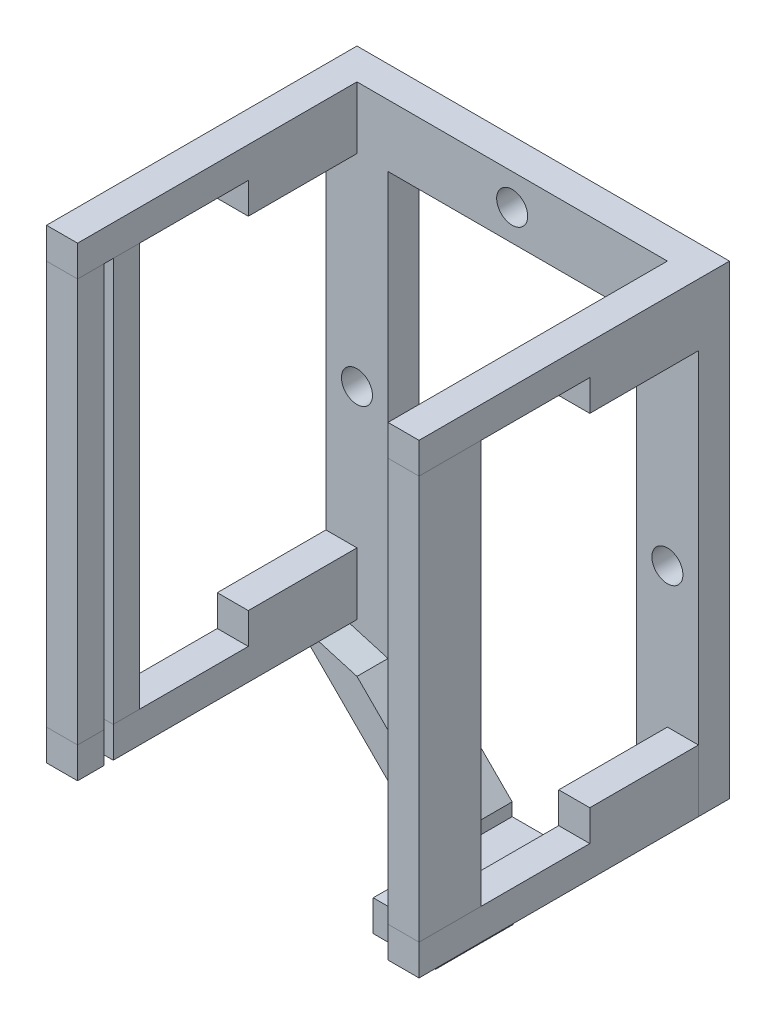
SolidWorks part; units mm, degrees
ref_plane "Plan de face" through (0, 0, 0) normal (0, 0, 1) x (1, 0, 0)
ref_plane "Plan de dessus" through (0, 0, 0) normal (0, 1, 0) x (1, 0, 0)
ref_plane "Plan de droite" through (0, 0, 0) normal (1, 0, 0) x (0, 0, -1)
sketch "Esquisse2" plane through (0, 0, 0) normal (0, 0, 1) x (1, 0, 0)
  line L0 (-70, 50) -> (-20, 0)
  line L1 (0, 0) -> (-20, 0)
  line L2 (50, 50) -> (50, 200)
  line L3 (50, 200) -> (-70, 200)
  line L4 (-70, 50) -> (-70, 200)
  line L5 (50, 50) -> (0, 0)
  line L6 (-50, 180) -> (30, 180)
  line L7 (30, 180) -> (30, 44.1421)
  line L8 (30, 44.1421) -> (0, 14.1421)
  line L9 (0, 14.1421) -> (-20, 14.1421)
  line L10 (-20, 14.1421) -> (-50, 44.1421)
  line L11 (-50, 44.1421) -> (-50, 180)
  line L12 (-20, 14.1421) -> (-20, 0) construction
  line L13 (0, 14.1421) -> (0, 0) construction
  line L14 (-50, 44.1421) -> (-70, 50) construction
  line L15 (30, 44.1421) -> (50, 50) construction
  dimension "D1" = 120
  dimension "D2" = 200
  dimension "D3" = 45
  dimension "D4" = 50
  dimension "D5" = 45
  dimension "D6" = 50
  dimension "D7" = 20
  dimension "D8" = 20
  dimension "D9" = 10
  dimension "D10" = 10
  dimension "D11" = 20
extrude "Extrusion2" add sketch "Esquisse2" along normal blind 20
sketch "Esquisse3" plane through (0, 0, 20) normal (0, 0, 1) x (1, 0, 0)
  line L0 (50, 200) -> (-70, 200) construction
  line L1 (-50, 180) -> (39.728, 180)
  line L2 (-50, 180) -> (-50, 200)
  line L3 (-50, 200) -> (39.728, 200)
  line L4 (39.728, 180) -> (39.728, 200)
  line L6 (30, 44.1421) -> (30, 180) construction
extrude "Enlèv. mat.-Extru.1" cut sketch "Esquisse3" against normal blind 10
sketch "Esquisse5" plane through (0, 0, 10) normal (0, 0, 1) x (1, 0, 0)
  line L0 (-70, 50) -> (-50, 44.1421)
  line L1 (-70, 200) -> (50, 200)
  line L2 (-70, 200) -> (-70, 50)
  line L4 (50, 200) -> (50, 50)
  line L5 (-50, 44.1421) -> (30, 44.1421)
  line L6 (30, 44.1421) -> (50, 50)
extrude "Enlèv. mat.-Extru.3" cut sketch "Esquisse5" along normal blind 50.7275
sketch "Esquisse6" plane through (0, 0, 10) normal (0, 0, 1) x (1, 0, 0)
  line L1 (-70, 200) -> (-60, 200)
  line L2 (-70, 200) -> (-70, 180)
  line L3 (-70, 180) -> (-60, 180)
  line L4 (-60, 200) -> (-60, 180)
  line L5 (50, 200) -> (40, 200)
  line L6 (50, 200) -> (50, 180)
  line L7 (50, 180) -> (40, 180)
  line L8 (40, 200) -> (40, 180)
  dimension "D1" = 20
  dimension "D2" = 20
  dimension "D3" = 10
  dimension "D4" = 10
extrude "Extrusion3" add sketch "Esquisse6" along normal blind 90
sketch "Esquisse7" plane through (0, 0, 100) normal (0, 0, 1) x (1, 0, 0)
  line L0 (-70, 200) -> (-70, 180) construction
  line L1 (-70, 190) -> (-60, 190)
  line L2 (-70, 190) -> (-70, 180)
  line L3 (-70, 180) -> (-60, 180)
  line L4 (-60, 190) -> (-60, 180)
  line L5 (40, 200) -> (40, 180) construction
  line L6 (40, 190) -> (50, 190)
  line L7 (40, 190) -> (40, 180)
  line L8 (40, 180) -> (50, 180)
  line L9 (50, 190) -> (50, 180)
extrude "Enlèv. mat.-Extru.4" cut sketch "Esquisse7" against normal blind 55
sketch "Esquisse8" plane through (0, 0, 10) normal (0, 0, 1) x (1, 0, 0)
  line L0 (-70, 180) -> (-70, 50) construction
  line L1 (-70, 50) -> (-60, 50)
  line L2 (-70, 50) -> (-70, 70)
  line L3 (-70, 70) -> (-60, 70)
  line L4 (-60, 50) -> (-60, 70)
  line L5 (-60, 200) -> (-70, 200) construction
  line L7 (50, 50) -> (40, 50)
  line L8 (50, 50) -> (50, 70)
  line L9 (50, 70) -> (40, 70)
  line L10 (40, 50) -> (40, 70)
  dimension "D1" = 20
  dimension "D2" = 10
  dimension "D3" = 150
  dimension "D4" = 20
  dimension "D5" = 10
extrude "Extrusion7" add sketch "Esquisse8" along normal blind 90 separate body
sketch "Esquisse9" plane through (-70, 0, 0) normal (-1, 0, 0) x (0, 0, 1)
  line L1 (100, 70) -> (45, 70)
  line L2 (100, 70) -> (100, 60)
  line L3 (100, 60) -> (45, 60)
  line L4 (45, 70) -> (45, 60)
  dimension "D1" = 55
  dimension "D2" = 10
extrude "Enlèv. mat.-Extru.5" cut sketch "Esquisse9" against normal blind 142.1416
sketch "Esquisse10" plane through (0, 0, 20) normal (0, 0, 1) x (1, 0, 0)
  line L0 (-20, 0) -> (0, 0) construction
  line L1 (-19.7577, 10) -> (0.2423, 10)
  line L2 (-19.7577, 10) -> (-19.7577, 0)
  line L3 (-19.7577, 0) -> (0.2423, 0)
  line L4 (0.2423, 10) -> (0.2423, 0)
  dimension "D1" = 10
  dimension "D2" = 20
extrude "Extrusion8" add sketch "Esquisse10" along normal blind 25
sketch "Esquisse11" plane through (50, 0, 0) normal (1, 0, 0) x (0, 0, -1)
  line L0 (-45, 60) -> (-100, 60) construction
  line L1 (-100, 190) -> (-80, 190)
  line L2 (-100, 190) -> (-100, 60)
  line L3 (-100, 60) -> (-80, 60)
  line L4 (-80, 190) -> (-80, 60)
  dimension "D1" = 20
extrude "Extrusion10" add sketch "Esquisse11" against normal blind 10 separate body
sketch "Esquisse12" plane through (-70, 0, 0) normal (-1, 0, 0) x (0, 0, 1)
  line L1 (100, 190) -> (80, 190)
  line L2 (100, 190) -> (100, 60)
  line L3 (100, 60) -> (80, 60)
  line L4 (80, 190) -> (80, 60)
extrude "Extrusion12" add sketch "Esquisse12" against normal blind 10 separate body
sketch "Esquisse13" plane through (40, 0, 0) normal (-1, 0, 0) x (0, 0, 1)
  line L0 (100, 60) -> (100, 190) construction
  line L1 (91.5, 190) -> (88.5, 190)
  line L2 (91.5, 190) -> (91.5, 50)
  line L3 (91.5, 50) -> (88.5, 50)
  line L4 (88.5, 190) -> (88.5, 50)
  line L5 (80, 190) -> (80, 60) construction
  line L7 (100, 190) -> (80, 190) construction
  line L9 (100, 50) -> (10, 50) construction
  dimension "D1" = 8.5
  dimension "D2" = 8.5
extrude "Enlèv. mat.-Extru.6" cut sketch "Esquisse13" against normal blind 5 and the other way blind 105
sketch "Esquisse14" plane through (40, 0, 0) normal (-1, 0, 0) x (0, 0, 1)
  line L0 (100, 50) -> (10, 50) construction
  line L1 (91.5, 61.07) -> (88.5, 61.07)
  line L2 (91.5, 61.07) -> (91.5, 50)
  line L3 (91.5, 50) -> (88.5, 50)
  line L4 (88.5, 61.07) -> (88.5, 50)
  line L5 (100, 60) -> (100, 50) construction
  dimension "D1" = 8.5
  dimension "D2" = 3
extrude "Enlèv. mat.-Extru.7" cut sketch "Esquisse14" against normal blind 5 and the other way blind 105
sketch "Esquisse15" plane through (0, 0, 0) normal (0, 0, -1) x (-1, 0, 0)
  line L0 (70, 200) -> (-50, 180) construction
  line L1 (-50, 50) -> (-30, 180) construction
  line L2 (50, 180) -> (70, 50) construction
  circle A0 centre (10, 190) radius 5
  circle A1 centre (-40, 115) radius 5
  circle A2 centre (60, 115) radius 5
  dimension "D1" = 10
  dimension "D2" = 10
  dimension "D3" = 10
extrude "Enlèv. mat.-Extru.8" cut sketch "Esquisse15" against normal blind 28.102
sketch "Esquisse16" plane through (0, 0, 20) normal (0, 0, 1) x (1, 0, 0)
  line L1 (-20, 14.1421) -> (0.2423, 14.1421)
  line L2 (-20, 14.1421) -> (-20, 10)
  line L3 (-20, 10) -> (0.2423, 10)
  line L4 (0.2423, 14.1421) -> (0.2423, 10)
extrude "Enlèv. mat.-Extru.9" cut sketch "Esquisse16" against normal blind 28.102
